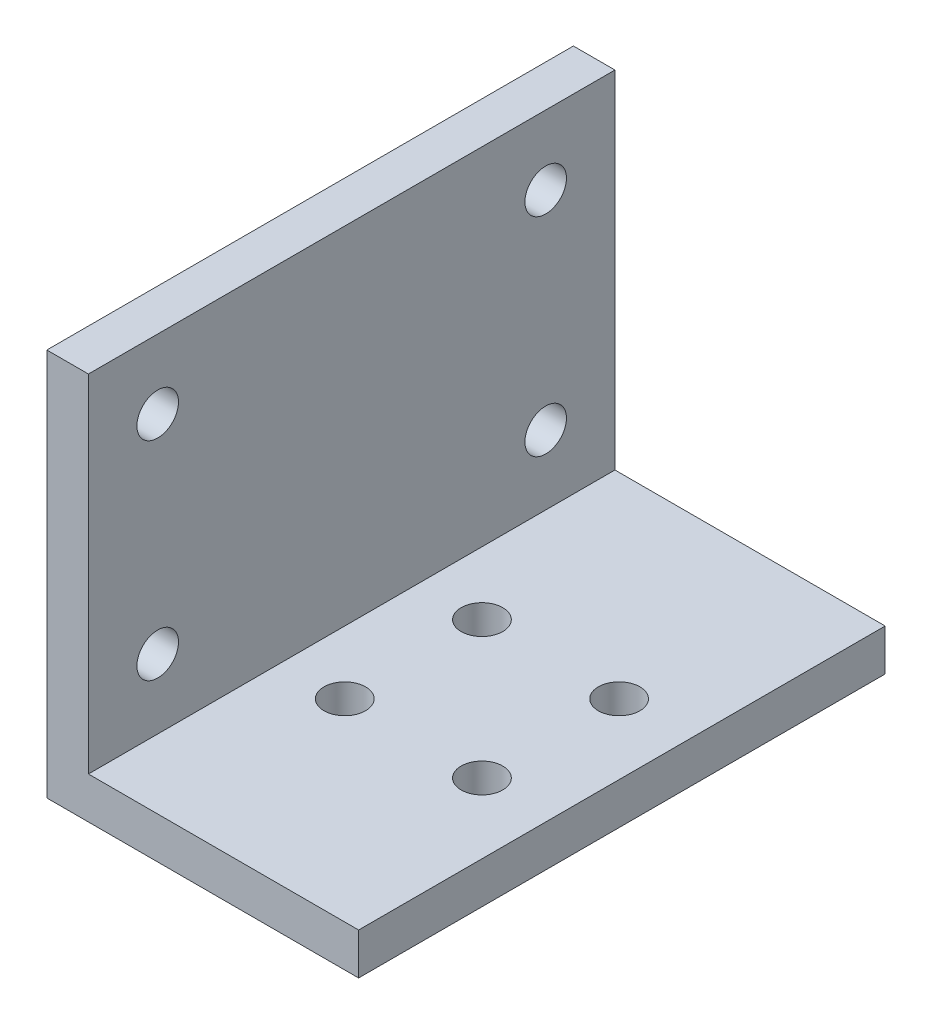
SolidWorks part; units mm, degrees
ref_plane "前视基准面" through (0, 0, 0) normal (0, 0, 1) x (1, 0, 0)
ref_plane "上视基准面" through (0, 0, 0) normal (0, 1, 0) x (1, 0, 0)
ref_plane "右视基准面" through (0, 0, 0) normal (1, 0, 0) x (0, 0, -1)
other "Configuration Table"
sketch "草图1" plane through (0, 0, 0) normal (0, 1, 0) x (1, 0, 0)
  line L1 (11.25, -19) -> (-11.25, -19)
  line L2 (11.25, -19) -> (11.25, 19)
  line L3 (11.25, 19) -> (-11.25, 19)
  line L4 (-11.25, -19) -> (-11.25, 19)
  line L5 (11.25, -19) -> (-11.25, 19) construction
  line L6 (11.25, 19) -> (-11.25, -19) construction
  point P0 (0, 0)
  dimension "D1" = 22.5
  dimension "D2" = 38
extrude "凸台-拉伸1" add sketch "草图1" along normal blind 3
sketch "草图2" plane through (0, 3, 0) normal (0, 1, 0) x (1, 0, 0)
  line L0 (-11.25, -19) -> (11.25, -19) construction
  line L1 (-11.25, 19) -> (-8.25, 19)
  line L2 (-11.25, 19) -> (-11.25, -19)
  line L3 (-11.25, -19) -> (-8.25, -19)
  line L4 (-8.25, 19) -> (-8.25, -19)
  dimension "D1" = 3
extrude "凸台-拉伸2" add sketch "草图2" along normal blind 25
sketch "草图3" plane through (0, 0, 0) normal (0, -1, 0) x (1, 0, 0)
  circle A0 centre (-3.6997, 5.0497) radius 1.5
  circle A1 centre (6.1997, 5.0497) radius 1.5
  circle A2 centre (-3.6997, -4.8497) radius 1.5
  circle A3 centre (6.1997, -4.8497) radius 1.5
extrude "切除-拉伸2" cut sketch "草图3" against normal blind 25
sketch "草图4" plane through (-8.25, 0, 0) normal (1, 0, 0) x (0, 0, -1)
  line L0 (19, 28) -> (19, 3) construction
  line L1 (-19, 28) -> (19, 28) construction
  line L2 (-19, 3) -> (19, 3) construction
  line L3 (-19, 28) -> (-19, 3) construction
  circle A0 centre (14, 23) radius 1.5
  circle A1 centre (-14, 23) radius 1.5
  circle A2 centre (-14, 8) radius 1.5
  circle A3 centre (14, 8) radius 1.5
  dimension "D1" = 3
  dimension "D4" = 5
  dimension "D2" = 5
  dimension "D3" = 5
  dimension "D5" = 5
  dimension "D6" = 5
  dimension "D7" = 5
  dimension "D8" = 5
  dimension "D9" = 5
extrude "切除-拉伸3" cut sketch "草图4" against normal blind 25
